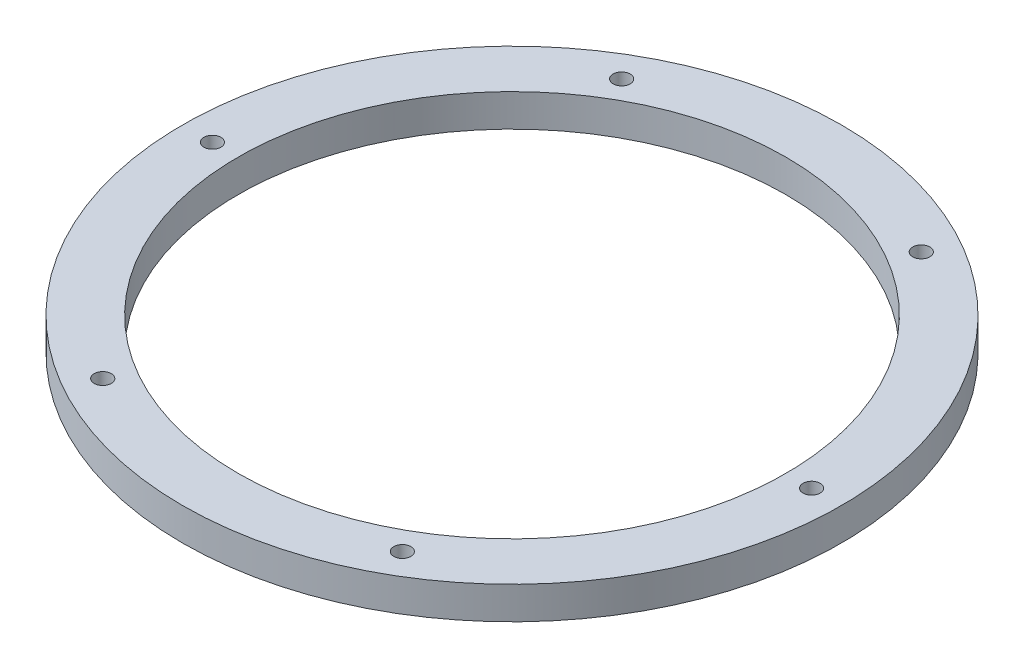
SolidWorks part; units mm, degrees
ref_plane "Front Plane" through (0, 0, 0) normal (0, 0, 1) x (1, 0, 0)
ref_plane "Top Plane" through (0, 0, 0) normal (0, 1, 0) x (1, 0, 0)
ref_plane "Right Plane" through (0, 0, 0) normal (1, 0, 0) x (0, 0, -1)
sketch "Sketch1" plane through (0, 0, 0) normal (0, 1, 0) x (1, 0, 0)
  line L0 (-1000, 0) -> (49000, 0) construction
  line L1 (0, -1000) -> (0, 49000) construction
  line L2 (-500, -866.0254) -> (24500, 42435.2448) construction
  line L3 (-500, 866.0254) -> (24500, -42435.2448) construction
  circle A0 centre (0, 0) radius 160
  circle A1 centre (0, 0) radius 192.5
  circle A3 centre (-87.5, 151.5544) radius 5
  circle A4 centre (-175, 0) radius 5
  circle A5 centre (87.5, 151.5544) radius 5
  circle A6 centre (175, 0) radius 5
  circle A7 centre (87.5, -151.5544) radius 5
  circle A8 centre (-87.5, -151.5544) radius 5
  dimension "D1" = 385
  dimension "D2" = 320
  dimension "D3" = 10
  dimension "D4" = 10
  dimension "D6" = 175
  dimension "D7" = 175
  dimension "D9" = 10
  dimension "D10" = 10
  dimension "D11" = 60
  dimension "D5" = 175
  dimension "D8" = 175
  dimension "D12" = 60
extrude "Boss-Extrude1" add sketch "Sketch1" along normal mid plane 19
